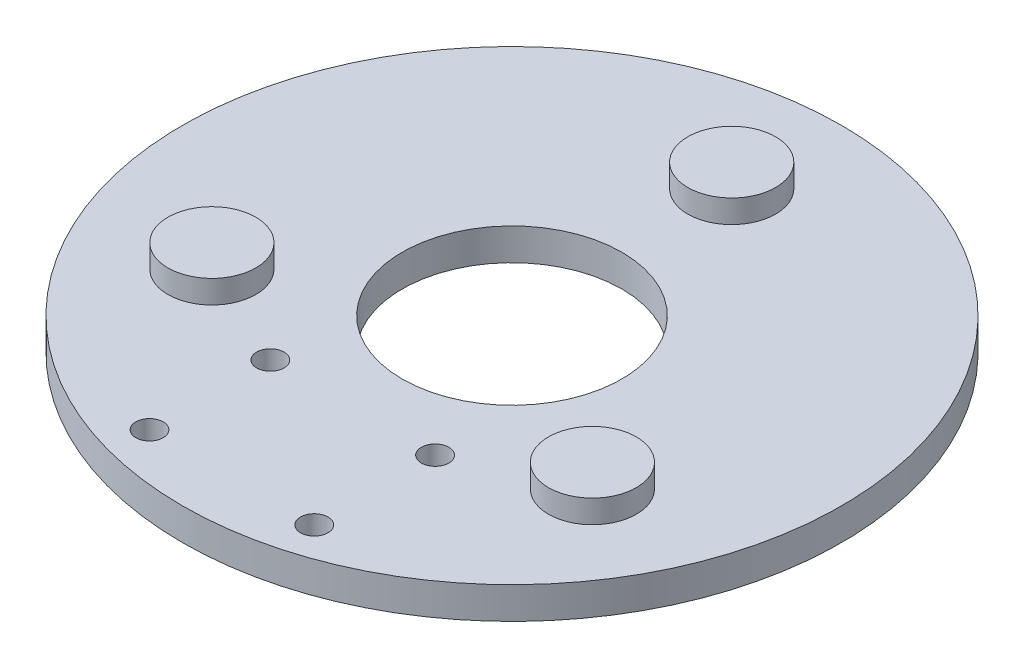
SolidWorks part; units mm, degrees
ref_plane "Front Plane" through (0, 0, 0) normal (0, 0, 1) x (1, 0, 0)
ref_plane "Top Plane" through (0, 0, 0) normal (0, 1, 0) x (1, 0, 0)
ref_plane "Right Plane" through (0, 0, 0) normal (1, 0, 0) x (0, 0, -1)
sketch "Sketch1" plane through (0, 0, 0) normal (0, 1, 0) x (1, 0, 0)
  circle A0 centre (0, 0) radius 25.4
  circle A1 centre (0, 0) radius 76.2
  dimension "D1" = 50.8
  dimension "D2" = 152.4
extrude "Boss-Extrude1" add sketch "Sketch1" along normal blind 7.366
sketch "Sketch2" plane through (0, 7.366, 0) normal (0, 1, 0) x (1, 0, 0)
  line L0 (0, 0) -> (-43.9941, -25.4) construction
  line L2 (0, 0) -> (0, 50.8) construction
  circle A0 centre (0, 50.8) radius 10.16
  circle A1 centre (-43.9941, -25.4) radius 10.16
  circle A2 centre (43.9941, -25.4) radius 10.16
  dimension "D1" = 3
  dimension "D2" = 20.32
extrude "Boss-Extrude2" add sketch "Sketch2" along normal blind 5.334
sketch "Sketch3" plane through (0, 7.366, 0) normal (0, 1, 0) x (1, 0, 0)
  line L0 (0, 0) -> (0, -76.2) construction
  line L1 (0, -30.48) -> (25.4, -30.48) construction
  line L2 (25.4, -30.48) -> (25.4, -71.12) construction
  line L3 (25.4, -71.12) -> (0, -71.12) construction
  line L5 (0, -25.4) -> (0, -76.2) construction
  circle A0 centre (0, 0) radius 76.2 construction
  circle A1 centre (-19.05, -64.77) radius 3.175
  circle A2 centre (0, 0) radius 25.4 construction
  circle A3 centre (19.05, -36.83) radius 3.175
  circle A4 centre (19.05, -64.77) radius 3.175
  circle A5 centre (-19.05, -36.83) radius 3.175
  dimension "D5" = 6.35
  dimension "D2" = 6.35
  dimension "D8" = 6.35
  dimension "D9" = 6.35
  dimension "D1" = 25.4
  dimension "D3" = 40.64
  dimension "D4" = 5.08
  dimension "D6" = 6.35
  dimension "D7" = 6.35
extrude "Cut-Extrude1" cut sketch "Sketch3" against normal through all
